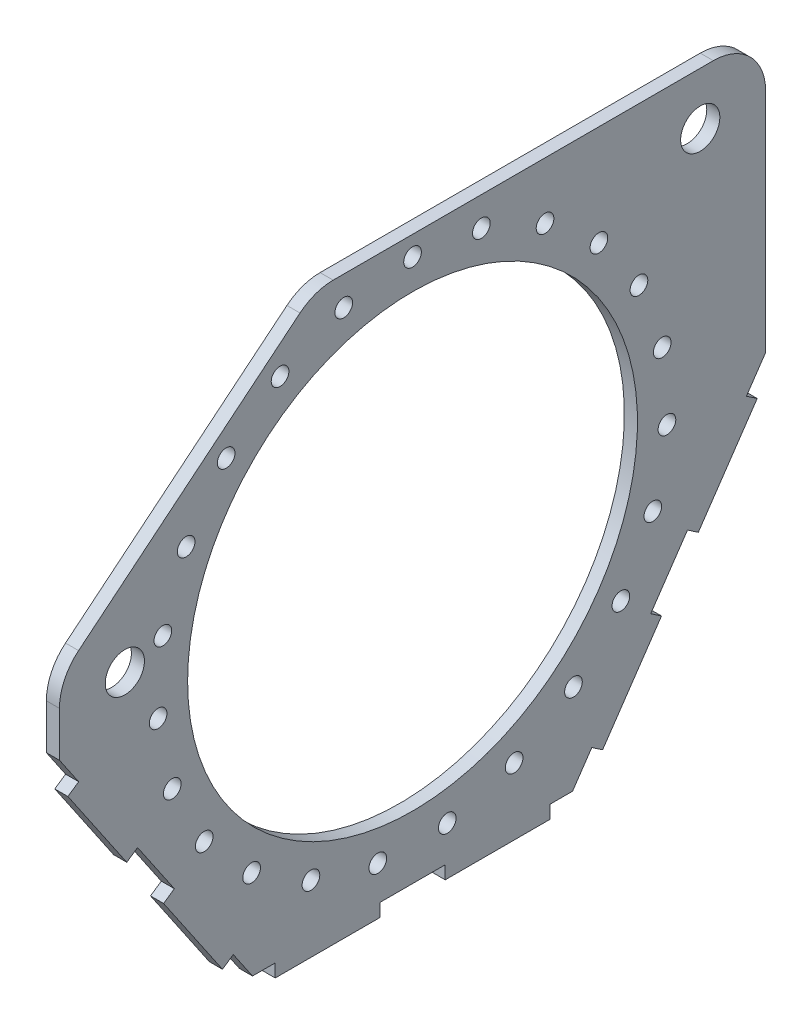
SolidWorks part; units mm, degrees
ref_plane "Plan de face" through (0, 0, 0) normal (0, 0, 1) x (1, 0, 0)
ref_plane "Plan de dessus" through (0, 0, 0) normal (0, 1, 0) x (1, 0, 0)
ref_plane "Plan de droite" through (0, 0, 0) normal (1, 0, 0) x (0, 0, -1)
sketch "Esquisse1" plane through (0, 0, 0) normal (1, 0, 0) x (0, 0, -1)
  line L0 (0, 0) -> (540, 0) construction
  line L1 (540, 0) -> (540, 340)
  line L2 (540, 340) -> (195, 340)
  line L3 (195, 340) -> (0, 180)
  line L4 (0, 180) -> (0, 0)
  line L5 (0, 180) -> (195, 180) construction
  line L6 (195, 180) -> (195, 340) construction
  line L7 (195, 180) -> (195, 0) construction
  line L8 (490, 0) -> (490, 300) construction
  line L9 (490, 300) -> (540, 300) construction
  line L10 (50, 160) -> (50, 0) construction
  line L11 (50, 0) -> (50, 160) construction
  line L12 (50, 160) -> (0, 160) construction
  line L13 (540, 0) -> (540, -100) construction
  line L14 (540, -100) -> (0, -100)
  line L15 (0, -100) -> (0, 0) construction
  line L26 (540, 0) -> (540, -100)
  line L29 (0, 0) -> (0, -100)
  circle A0 centre (490, 300) radius 15
  circle A1 centre (50, 160) radius 15
  dimension "D1" = 30
  dimension "D2" = 30
  dimension "D3" = 40
  dimension "D4" = 20
  dimension "D5" = 440
  dimension "D6" = 100
  dimension "D7" = 50
  dimension "D8" = 50
  dimension "D9" = 195
  dimension "D10" = 180
  dimension "D11" = 140
extrude "Boss.-Extru.1" add sketch "Esquisse1" along normal blind 10
sketch "Esquisse5" plane through (0, 0, 0) normal (-1, 0, 0) x (0, 0, 1)
  line L1 (-540, 130) -> (0, 130) construction
  line L2 (-540, 340) -> (-195, 340) construction
  line L3 (-540, -100) -> (-540, 340) construction
  line L4 (-270, -65) -> (-270, -100) construction
  line L6 (0, -100) -> (-540, -100) construction
  line L8 (-270, 325) -> (-270, 130) construction
  line L9 (-270, 130) -> (-270, -65) construction
  line L10 (-397.6704, -100) -> (-142.3296, -100)
  line L11 (-270, 130) -> (-322.6104, 317.7689) construction
  line L12 (-142.3296, -100) -> (0, 108.9485)
  line L13 (0, 180) -> (0, -100) construction
  line L14 (-190.7279, -100) -> (0, 180) construction
  line L15 (0, 180) -> (0, -100) construction
  line L17 (-397.6704, -100) -> (-540, 108.9485)
  line L18 (0, 108.9485) -> (0, -195.1894)
  line L19 (0, -195.1894) -> (-540, -195.1894)
  line L20 (-540, -195.1894) -> (-540, 108.9485)
  circle A1 centre (-270, 130) radius 195 construction
  circle A2 centre (-270, 325) radius 6.75
  circle A3 centre (-217.3896, 317.7689) radius 6.75
  circle A9 centre (-270, 130) radius 172
  circle A10 centre (-168.6811, 296.6118) radius 6.75
  circle A11 centre (-127.487, 263.0979) radius 6.75
  circle A12 centre (-96.8624, 219.7127) radius 6.75
  circle A13 centre (-79.0786, 169.6739) radius 6.75
  circle A14 centre (-75.4546, 116.6927) radius 6.75
  circle A15 centre (-86.2591, 64.6985) radius 6.75
  circle A16 centre (-110.6909, 17.5473) radius 6.75
  circle A17 centre (-146.9379, -21.2637) radius 6.75
  circle A18 centre (-192.3118, -48.8562) radius 6.75
  circle A19 centre (-243.4475, -63.1838) radius 6.75
  circle A20 centre (-296.5525, -63.1838) radius 6.75
  circle A21 centre (-347.6882, -48.8562) radius 6.75
  circle A22 centre (-393.0621, -21.2637) radius 6.75
  circle A23 centre (-429.3091, 17.5473) radius 6.75
  circle A24 centre (-453.7409, 64.6985) radius 6.75
  circle A25 centre (-464.5454, 116.6927) radius 6.75
  circle A26 centre (-460.9214, 169.6739) radius 6.75
  circle A27 centre (-443.1376, 219.7127) radius 6.75
  circle A28 centre (-412.513, 263.0979) radius 6.75
  circle A29 centre (-371.3189, 296.6118) radius 6.75
  circle A30 centre (-322.6104, 317.7689) radius 6.75
  point P26 (-270, 130)
  point P31 (-270, 130)
  point P78 (-270, 130)
  point P84 (-270, 130)
  dimension "D5" = 344
  dimension "D9" = 390
  dimension "D12" = 13.5
  dimension "D3" = 210
  dimension "D4" = 40
  dimension "D10" = 15.652
  dimension "D11" = 23
extrude "Enlèv. mat.-Extru.1" cut sketch "Esquisse5" against normal blind 10
fillet "Congé1" radius 40 3 edges at (5, 340, -540) (5, 180, 0) (5, 340, -195)
sketch "Esquisse6" plane through (10, 0, 0) normal (1, 0, 0) x (0, 0, -1)
  line L0 (0, 126.7113) -> (147.6175, -90) construction
  line L1 (0, 161.079) -> (0, 108.9485) construction
  line L2 (147.6175, -90) -> (392.3825, -90) construction
  line L3 (392.3825, -90) -> (540, 126.7113) construction
  line L4 (540, 108.9485) -> (540, 300) construction
  line L5 (397.6704, -100) -> (540, 108.9485) construction
  line L6 (270, 130) -> (270, -90) construction
  line L7 (0, 108.9485) -> (142.3296, -100) construction
  line L8 (142.3296, -100) -> (397.6704, -100) construction
  line L9 (540, -146.2098) -> (540, 126.7113)
  line L10 (540, -146.2098) -> (0, -146.2098)
  line L11 (0, -146.2098) -> (0, 126.7113)
  line L12 (0, 126.7113) -> (14.6967, 105.1357)
  line L13 (14.6967, 105.1357) -> (6.432, 99.506)
  line L14 (6.432, 99.506) -> (51.4697, 33.3879)
  line L15 (51.4697, 33.3879) -> (59.7344, 39.0176)
  line L16 (59.7344, 39.0176) -> (87.883, -2.3062)
  line L17 (87.883, -2.3062) -> (79.6183, -7.9359)
  line L18 (79.6183, -7.9359) -> (124.656, -74.054)
  line L19 (124.656, -74.054) -> (132.9208, -68.4243)
  line L20 (132.9208, -68.4243) -> (147.6175, -90)
  line L21 (147.6175, -90) -> (165, -90)
  line L22 (165, -90) -> (165, -100)
  line L23 (165, -100) -> (245, -100)
  line L24 (245, -100) -> (245, -90)
  line L25 (245, -90) -> (295, -90)
  line L26 (540, 126.7113) -> (525.3033, 105.1357)
  line L27 (466.1913, 18.3557) -> (73.8087, 18.3557) construction
  line L28 (525.3033, 105.1357) -> (533.568, 99.506)
  line L29 (533.568, 99.506) -> (488.5303, 33.3879)
  line L30 (488.5303, 33.3879) -> (480.2656, 39.0176)
  line L31 (480.2656, 39.0176) -> (452.117, -2.3062)
  line L32 (452.117, -2.3062) -> (460.3817, -7.9359)
  line L33 (460.3817, -7.9359) -> (415.344, -74.054)
  line L34 (415.344, -74.054) -> (407.0792, -68.4243)
  line L35 (407.0792, -68.4243) -> (392.3825, -90)
  line L36 (392.3825, -90) -> (375, -90)
  line L37 (375, -90) -> (375, -100)
  line L38 (375, -100) -> (295, -100)
  line L39 (295, -100) -> (295, -90)
  point P33 (73.8087, 18.3557)
  point P34 (270, 130)
  point P49 (270, -90)
  dimension "D1" = 10
  dimension "D2" = 50
  dimension "D3" = 10
  dimension "D4" = 80
  dimension "D5" = 80
  dimension "D6" = 50
  dimension "D7" = 80
extrude "Enlèv. mat.-Extru.2" cut sketch "Esquisse6" against normal blind 10
